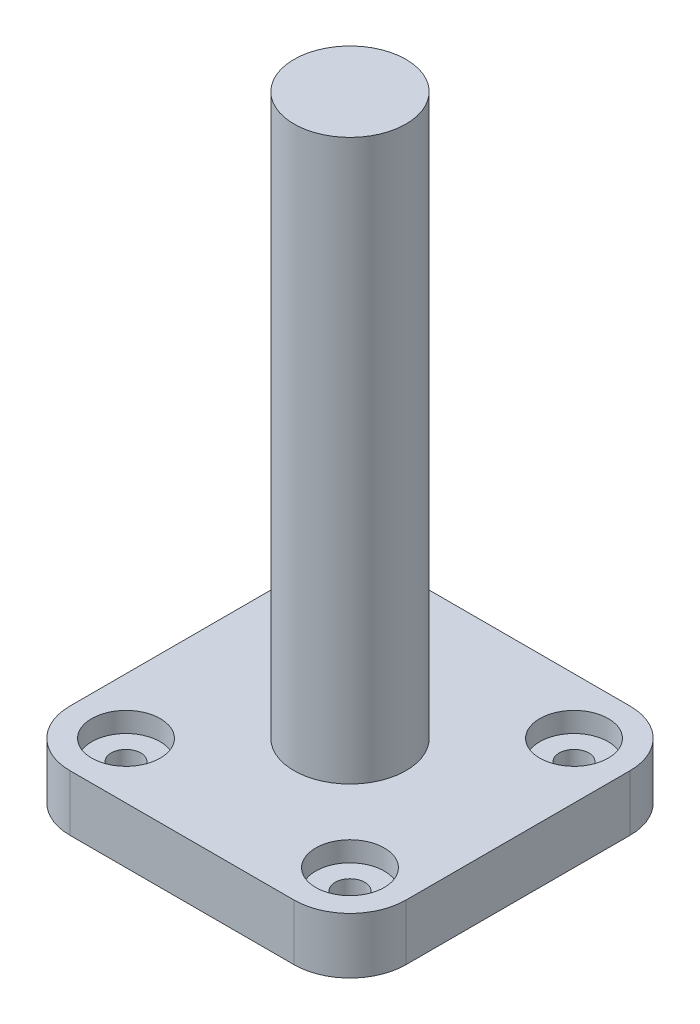
SolidWorks part; units mm, degrees
ref_plane "Front Plane" through (0, 0, 0) normal (0, 0, 1) x (1, 0, 0)
ref_plane "Top Plane" through (0, 0, 0) normal (0, 1, 0) x (1, 0, 0)
ref_plane "Right Plane" through (0, 0, 0) normal (1, 0, 0) x (0, 0, -1)
sketch "Sketch1" plane through (0, 0, 0) normal (0, 1, 0) x (1, 0, 0)
  line L1 (-20, -30) -> (20, -30)
  line L2 (-30, -20) -> (-30, 20)
  line L3 (-20, 30) -> (20, 30)
  line L4 (30, -20) -> (30, 20)
  line L5 (-30, -30) -> (30, 30) construction
  line L6 (-30, 30) -> (30, -30) construction
  arc A0 (-20, -30) -> (-30, -20) centre (-20, -20) cw
  arc A1 (20, -30) -> (30, -20) centre (20, -20) ccw
  arc A2 (20, 30) -> (30, 20) centre (20, 20) cw
  arc A3 (-30, 20) -> (-20, 30) centre (-20, 20) cw
  point P0 (0, 0)
  dimension "D2" = 10
  dimension "D1" = 60
extrude "Boss-Extrude1" add sketch "Sketch1" along normal blind 10
sketch "Sketch6" plane through (0, 10, 0) normal (0, 1, 0) x (1, 0, 0)
  point P0 (-20, -20)
  point P3 (-20, 20)
  point P6 (20, 20)
  point P9 (20, -20)
hole_wizard "CBORE for M5 Hex Head Bolt1" positions "Sketch6" profile "Sketch5" counterbore size "M5" standard "ANSI Metric" end condition through all
sketch "Sketch5" plane through (-20, 10, 20) normal (1, 0, 0) x (0, 0, 1)
  line L0 (0, 0) -> (0, 10)
  line L1 (0, 10) -> (2.65, 10)
  line L3 (2.65, 10) -> (2.65, 3.58)
  line L4 (2.65, 3.58) -> (6.12, 3.58)
  line L5 (6.12, 3.58) -> (6.12, 0)
  line L7 (6.12, 0) -> (0, 0)
  line L11 (0, -6.35) -> (0, 107.95) construction
  dimension "Thru Hole Dia." = 5.3
  dimension "Thru Hole Depth" = 10
  dimension "C'Bore Dia." = 12.24
  dimension "C'Bore Depth" = 3.58
sketch "Sketch7" plane through (0, 10, 0) normal (0, 1, 0) x (1, 0, 0)
  circle A0 centre (0, 0) radius 10
  dimension "D1" = 20
extrude "Boss-Extrude2" add sketch "Sketch7" along normal blind 100
